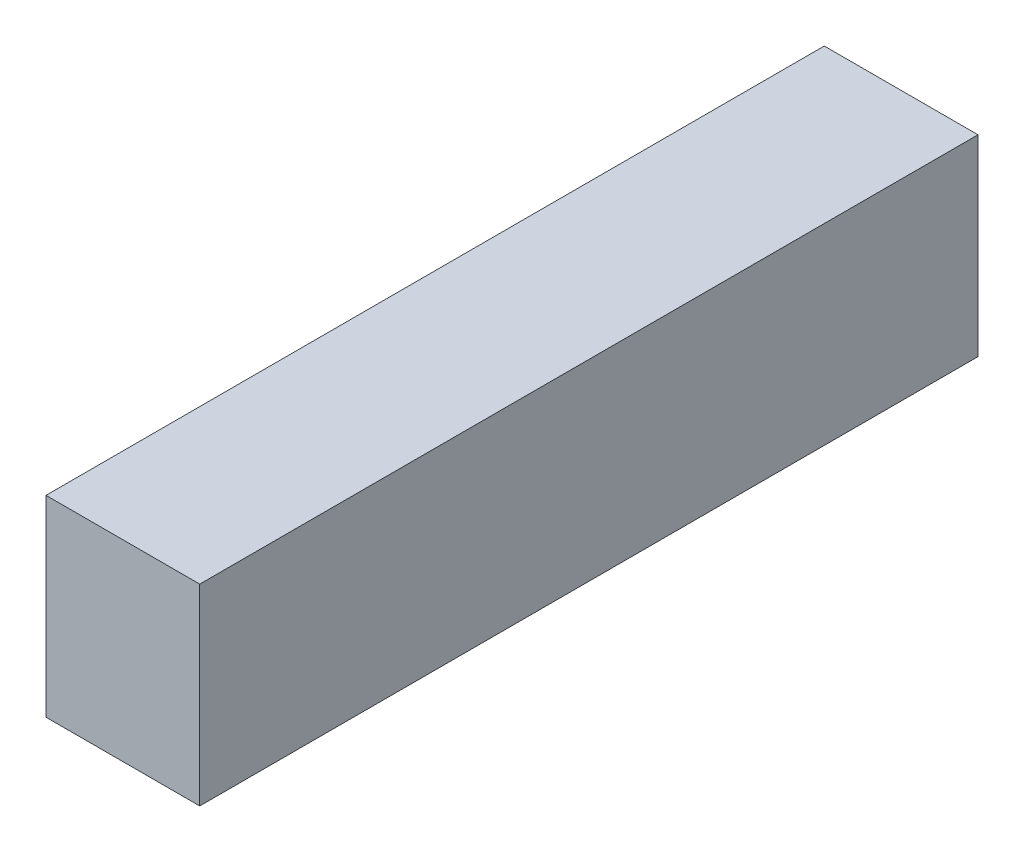
SolidWorks part; units mm, degrees
ref_plane "前视基准面" through (0, 0, 0) normal (0, 0, 1) x (1, 0, 0)
ref_plane "上视基准面" through (0, 0, 0) normal (0, 1, 0) x (1, 0, 0)
ref_plane "右视基准面" through (0, 0, 0) normal (1, 0, 0) x (0, 0, -1)
other "Configuration Table"
sketch "草图1" plane through (0, 0, 0) normal (0, 1, 0) x (1, 0, 0)
  line L1 (-160, -810) -> (160, -810)
  line L2 (-160, -810) -> (-160, 810)
  line L3 (-160, 810) -> (160, 810)
  line L4 (160, -810) -> (160, 810)
  line L5 (-160, -810) -> (160, 810) construction
  line L6 (-160, 810) -> (160, -810) construction
  point P0 (0, 0)
  dimension "D1" = 320
  dimension "D2" = 1620
extrude "凸台-拉伸1" add sketch "草图1" along normal blind 400
sketch "草图2" plane through (0, 0, 810) normal (0, 0, 1) x (1, 0, 0)
  line L0 (-160, 0) -> (160, 0) construction
  line L1 (-25, 0) -> (25, 0)
  line L2 (-25, 0) -> (-25, 100)
  line L3 (-25, 100) -> (25, 100)
  line L4 (25, 0) -> (25, 100)
  dimension "D1" = 50
  dimension "D2" = 100
sketch "草图3" plane through (0, 400, 0) normal (0, 1, 0) x (1, 0, 0)
  line L0 (160, 810) -> (-160, 810) construction
  line L1 (-150, -810) -> (150, -810)
  line L2 (-150, -810) -> (-150, 810)
  line L3 (-150, 810) -> (150, 810)
  line L4 (150, -810) -> (150, 810)
  line L5 (-150, -810) -> (150, 810) construction
  line L6 (-150, 810) -> (150, -810) construction
  point P0 (0, 0)
  dimension "D1" = 300
